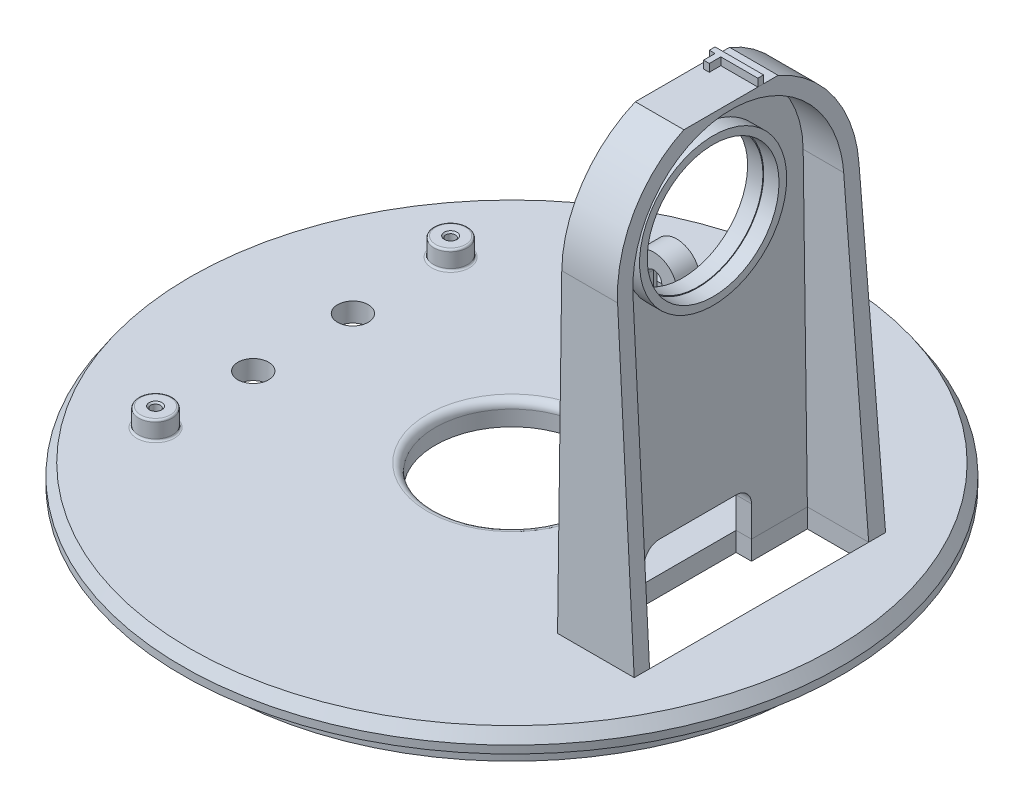
SolidWorks part; units mm, degrees
ref_plane "Plan de face" through (0, 0, 0) normal (0, 0, 1) x (1, 0, 0)
ref_plane "Plan de dessus" through (0, 0, 0) normal (0, 1, 0) x (1, 0, 0)
ref_plane "Plan de droite" through (0, 0, 0) normal (1, 0, 0) x (0, 0, -1)
sketch "Esquisse1" plane through (0, 0, 0) normal (1, 0, 0) x (0, 0, -1)
  line L0 (0, -26.723) -> (0, 41.89) construction
  line L1 (38.5, 0) -> (38.5, 4)
  line L2 (38.5, 4) -> (43, 4)
  line L3 (43, 4) -> (43, 5)
  line L4 (42, 6.5) -> (10, 6.5)
  line L5 (10, 6.5) -> (10, 3.5)
  line L6 (10, 3.5) -> (11, 3.5)
  line L7 (11, 3.5) -> (11, 4)
  line L8 (11, 4) -> (36.9, 4)
  line L9 (36.9, 4) -> (36.9, 0)
  line L10 (36.9, 0) -> (38.5, 0)
  line L11 (0, 0) -> (59.5639, 0) construction
  line L12 (43, 5) -> (42, 6.5)
  dimension "D1" = 10
  dimension "D2" = 0.5
  dimension "D3" = 1
  dimension "D4" = 43
  dimension "D5" = 4
  dimension "D6" = 1.6
  dimension "D7" = 4
  dimension "D8" = 4.5
  dimension "D9" = 2.5
  dimension "D10" = 1
  dimension "D11" = 1
revolve "Révolution1" add sketch "Esquisse1" angle 360 about L0
sketch "Esquisse2" plane through (0, 4, 0) normal (0, -1, 0) x (1, 0, 0)
  line L0 (0, 0) -> (0, -52.5963) construction
  line L1 (0, 0) -> (-60.9016, 0) construction
  line L2 (0, 0) -> (35.2447, -61.0455) construction
  circle A0 centre (0, 0) radius 16 construction
  circle A1 centre (-16, 0) radius 3
  dimension "D3" = 32
  dimension "D4" = 6
  dimension "D1" = 270
  dimension "D2" = 120
extrude "Boss.-Extru.1" add sketch "Esquisse2" along normal blind 3
pattern_circular "Répétition circulaire1" count 3 over 360 about axis through (0, 0, 0) along (0, 1, 0) of "Boss.-Extru.1"
sketch "Esquisse3" plane through (0, 6.5, 0) normal (0, 1, 0) x (1, 0, 0)
  line L0 (0, 0) -> (-69.5596, 0) construction
  line L1 (-22.25, 41.5926) -> (-22.25, -45.3568) construction
  line L2 (-27.25, 41.5926) -> (-27.25, -45.3568) construction
  circle A0 centre (-27.25, 19.25) radius 1
  circle A1 centre (-27.25, -19.25) radius 1
  circle A2 centre (-27.25, 6.5) radius 2
  circle A3 centre (-27.25, -6.5) radius 2
  dimension "D4" = 19.25
  dimension "D5" = 2
  dimension "D6" = 2
  dimension "D8" = 6.5
  dimension "D9" = 4
  dimension "D10" = 4
  dimension "D1" = 22.25
  dimension "D3" = 38.5
  dimension "D7" = 13
  dimension "D2" = 5
extrude "Enlèv. mat.-Extru.1" cut sketch "Esquisse3" against normal through all contours A2 | A3
ref_plane "Plan1" through (22.25, 0, 0) normal (1, 0, 0) x (0, 0, -1)
sketch "Esquisse4" plane through (22.25, 0, 0) normal (1, 0, 0) x (0, 0, -1)
  line L0 (-14.5, -8.6604) -> (-13.7488, 47.185) construction
  line L2 (0, -8.9601) -> (0, 72.3786) construction
  line L3 (-16.2962, 6.5) -> (-15.7486, 47.2119)
  line L4 (16.5, 6.5) -> (15.7486, 47.2119)
  line L5 (-16.4998, -8.6335) -> (-15.7486, 47.2119) construction
  line L6 (-16.2962, 6.5) -> (16.5, 6.5)
  line L7 (42, 6.5) -> (-42, 6.5) construction
  arc A0 (0, 60.75) -> (-13.7488, 47.185) centre (0, 47) ccw construction
  arc A1 (0, 62.75) -> (-15.7486, 47.2119) centre (0, 47) ccw
  arc A2 (0, 62.75) -> (15.7486, 47.2119) centre (0, 47) cw
  circle A3 centre (0, 47) radius 8.5
  point P2 (-14.2961, 6.5)
  dimension "D1" = 27.5
  dimension "D2" = 40.5
  dimension "D5" = 17
  dimension "D3" = 14.2961
  dimension "D6" = 16.5
  dimension "D4" = 2
extrude "Boss.-Extru.2" add sketch "Esquisse4" along normal blind 10 separate body
ref_plane "Plan2" through (0, 0, 16.2962) normal (0, 0, 1) x (1, 0, 0)
sketch "Esquisse7" plane through (32.25, 0, 0) normal (1, 0, 0) x (0, 0, -1)
  line L0 (-14.5, -8.6604) -> (-13.7488, 47.185) construction
  line L1 (-14.5, -8.6604) -> (-13.7488, 47.185)
  line L2 (0, -8.9601) -> (0, 72.3786) construction
  line L3 (0, -8.9601) -> (0, 72.3786) construction
  line L4 (14.5, -8.6604) -> (13.7488, 47.185)
  line L5 (-14.5, -8.6604) -> (14.5, -8.6604)
  arc A0 (0, 60.75) -> (-13.7488, 47.185) centre (0, 47) ccw construction
  arc A1 (13.7488, 47.185) -> (-13.7488, 47.185) centre (0, 47) ccw
extrude "Enlèv. mat.-Extru.3" cut sketch "Esquisse7" against normal blind 8
sketch "Esquisse6" plane through (0, 0, 16.2962) normal (0, 0, 1) x (1, 0, 0)
  line L0 (32.25, 6.5) -> (28.5, 62.75)
  line L1 (32.25, 62.75) -> (22.25, 62.75) construction
  line L2 (28.5, 62.75) -> (32.25, 62.75)
  line L3 (32.25, 62.75) -> (32.25, 6.5)
  line L4 (22.25, -44.7363) -> (22.25, 44.7363) construction
  dimension "D1" = 6.25
extrude "Enlèv. mat.-Extru.2" cut sketch "Esquisse6" against normal through all
sketch "Esquisse8" plane through (0, 6.5, 0) normal (0, 1, 0) x (-1, 0, 0)
  line L1 (-24.25, -14.2961) -> (-32.25, -14.2961)
  line L2 (-24.25, -14.2961) -> (-24.25, 14.2961)
  line L3 (-24.25, 14.2961) -> (-32.25, 14.2961)
  line L4 (-32.25, -14.2961) -> (-32.25, 14.2961)
extrude "Enlèv. mat.-Extru.4" cut sketch "Esquisse8" against normal through all
fillet "Congé1" radius 0.5 3 edges at (-16, 4, -3) (10.5981, 4, -12.3564) (5.4019, 4, 15.3564)
sketch "Esquisse9" plane through (0, 1, 0) normal (0, -1, 0) x (1, 0, 0)
  arc B0 (8.2491, -12.3772) -> (7.7509, -12.3772) centre (8, -12.3564) ccw
  arc B1 (7.4762, -12.4508) -> (7.0447, -12.7) centre (7.25, -12.5574) ccw
  arc B2 (6.8436, -12.9011) -> (6.5944, -13.3326) centre (6.701, -13.1064) ccw
  arc B3 (6.5208, -13.6073) -> (6.5208, -14.1055) centre (6.5, -13.8564) ccw
  arc B4 (6.5944, -14.3802) -> (6.8436, -14.8117) centre (6.701, -14.6064) ccw
  arc B5 (7.0447, -15.0128) -> (7.4762, -15.262) centre (7.25, -15.1554) ccw
  arc B6 (7.7509, -15.3356) -> (8.2491, -15.3356) centre (8, -15.3564) ccw
  arc B7 (8.5238, -15.262) -> (8.9553, -15.0128) centre (8.75, -15.1554) ccw
  arc B8 (9.1564, -14.8117) -> (9.4056, -14.3802) centre (9.299, -14.6064) ccw
  arc B9 (9.4792, -14.1055) -> (9.4792, -13.6073) centre (9.5, -13.8564) ccw
  arc B10 (9.4056, -13.3326) -> (9.1564, -12.9011) centre (9.299, -13.1064) ccw
  arc B11 (8.9553, -12.7) -> (8.5238, -12.4508) centre (8.75, -12.5574) ccw
  arc B12 (8.5238, -12.4508) -> (8.2491, -12.3772) centre (8, -13.8564) ccw
  arc B13 (7.7509, -12.3772) -> (7.4762, -12.4508) centre (8, -13.8564) ccw
  arc B14 (7.0447, -12.7) -> (6.8436, -12.9011) centre (8, -13.8564) ccw
  arc B15 (6.5944, -13.3326) -> (6.5208, -13.6073) centre (8, -13.8564) ccw
  arc B16 (6.5208, -14.1055) -> (6.5944, -14.3802) centre (8, -13.8564) ccw
  arc B17 (6.8436, -14.8117) -> (7.0447, -15.0128) centre (8, -13.8564) ccw
  arc B18 (7.4762, -15.262) -> (7.7509, -15.3356) centre (8, -13.8564) ccw
  arc B19 (8.2491, -15.3356) -> (8.5238, -15.262) centre (8, -13.8564) ccw
  arc B20 (8.9553, -15.0128) -> (9.1564, -14.8117) centre (8, -13.8564) ccw
  arc B21 (9.4056, -14.3802) -> (9.4792, -14.1055) centre (8, -13.8564) ccw
  arc B22 (9.4792, -13.6073) -> (9.4056, -13.3326) centre (8, -13.8564) ccw
  arc B23 (9.1564, -12.9011) -> (8.9553, -12.7) centre (8, -13.8564) ccw
  arc B24 (-16.1422, 1.4932) -> (-16.6235, 1.3643) centre (-16.3882, 1.4489) ccw
  arc B25 (-16.8698, 1.2221) -> (-17.2221, 0.8698) centre (-17.0607, 1.0607) ccw
  arc B26 (-17.3643, 0.6235) -> (-17.4932, 0.1422) centre (-17.4489, 0.3882) ccw
  arc B27 (-17.4932, -0.1422) -> (-17.3643, -0.6235) centre (-17.4489, -0.3882) ccw
  arc B28 (-17.2221, -0.8698) -> (-16.8698, -1.2221) centre (-17.0607, -1.0607) ccw
  arc B29 (-16.6235, -1.3643) -> (-16.1422, -1.4932) centre (-16.3882, -1.4489) ccw
  arc B30 (-15.8578, -1.4932) -> (-15.3765, -1.3643) centre (-15.6118, -1.4489) ccw
  arc B31 (-15.1302, -1.2221) -> (-14.7779, -0.8698) centre (-14.9393, -1.0607) ccw
  arc B32 (-14.6357, -0.6235) -> (-14.5068, -0.1422) centre (-14.5511, -0.3882) ccw
  arc B33 (-14.5068, 0.1422) -> (-14.6357, 0.6235) centre (-14.5511, 0.3882) ccw
  arc B34 (-14.7779, 0.8698) -> (-15.1302, 1.2221) centre (-14.9393, 1.0607) ccw
  arc B35 (-15.3765, 1.3643) -> (-15.8578, 1.4932) centre (-15.6118, 1.4489) ccw
  arc B36 (-15.8578, 1.4932) -> (-16.1422, 1.4932) centre (-16, 0) ccw
  arc B37 (-16.6235, 1.3643) -> (-16.8698, 1.2221) centre (-16, 0) ccw
  arc B38 (-17.2221, 0.8698) -> (-17.3643, 0.6235) centre (-16, 0) ccw
  arc B39 (-17.4932, 0.1422) -> (-17.4932, -0.1422) centre (-16, 0) ccw
  arc B40 (-17.3643, -0.6235) -> (-17.2221, -0.8698) centre (-16, 0) ccw
  arc B41 (-16.8698, -1.2221) -> (-16.6235, -1.3643) centre (-16, 0) ccw
  arc B42 (-16.1422, -1.4932) -> (-15.8578, -1.4932) centre (-16, 0) ccw
  arc B43 (-15.3765, -1.3643) -> (-15.1302, -1.2221) centre (-16, 0) ccw
  arc B44 (-14.7779, -0.8698) -> (-14.6357, -0.6235) centre (-16, 0) ccw
  arc B45 (-14.5068, -0.1422) -> (-14.5068, 0.1422) centre (-16, 0) ccw
  arc B46 (-14.6357, 0.6235) -> (-14.7779, 0.8698) centre (-16, 0) ccw
  arc B47 (-15.1302, 1.2221) -> (-15.3765, 1.3643) centre (-16, 0) ccw
  arc B48 (8.2491, 15.3356) -> (7.7509, 15.3356) centre (8, 15.3564) ccw
  arc B49 (7.4762, 15.262) -> (7.0447, 15.0128) centre (7.25, 15.1554) ccw
  arc B50 (6.8436, 14.8117) -> (6.5944, 14.3802) centre (6.701, 14.6064) ccw
  arc B51 (6.5208, 14.1055) -> (6.5208, 13.6073) centre (6.5, 13.8564) ccw
  arc B52 (6.5944, 13.3326) -> (6.8436, 12.9011) centre (6.701, 13.1064) ccw
  arc B53 (7.0447, 12.7) -> (7.4762, 12.4508) centre (7.25, 12.5574) ccw
  arc B54 (7.7509, 12.3772) -> (8.2491, 12.3772) centre (8, 12.3564) ccw
  arc B55 (8.5238, 12.4508) -> (8.9553, 12.7) centre (8.75, 12.5574) ccw
  arc B56 (9.1564, 12.9011) -> (9.4056, 13.3326) centre (9.299, 13.1064) ccw
  arc B57 (9.4792, 13.6073) -> (9.4792, 14.1055) centre (9.5, 13.8564) ccw
  arc B58 (9.4056, 14.3802) -> (9.1564, 14.8117) centre (9.299, 14.6064) ccw
  arc B59 (8.9553, 15.0128) -> (8.5238, 15.262) centre (8.75, 15.1554) ccw
  arc B60 (8.5238, 15.262) -> (8.2491, 15.3356) centre (8, 13.8564) ccw
  arc B61 (7.7509, 15.3356) -> (7.4762, 15.262) centre (8, 13.8564) ccw
  arc B62 (7.0447, 15.0128) -> (6.8436, 14.8117) centre (8, 13.8564) ccw
  arc B63 (6.5944, 14.3802) -> (6.5208, 14.1055) centre (8, 13.8564) ccw
  arc B64 (6.5208, 13.6073) -> (6.5944, 13.3326) centre (8, 13.8564) ccw
  arc B65 (6.8436, 12.9011) -> (7.0447, 12.7) centre (8, 13.8564) ccw
  arc B66 (7.4762, 12.4508) -> (7.7509, 12.3772) centre (8, 13.8564) ccw
  arc B67 (8.2491, 12.3772) -> (8.5238, 12.4508) centre (8, 13.8564) ccw
  arc B68 (8.9553, 12.7) -> (9.1564, 12.9011) centre (8, 13.8564) ccw
  arc B69 (9.4056, 13.3326) -> (9.4792, 13.6073) centre (8, 13.8564) ccw
  arc B70 (9.4792, 14.1055) -> (9.4056, 14.3802) centre (8, 13.8564) ccw
  arc B71 (9.1564, 14.8117) -> (8.9553, 15.0128) centre (8, 13.8564) ccw
sketch_block_instance "Bloc1-1"
sketch_block "Bloc1"
sketch_block_instance "Bloc1-2"
sketch_block_instance "Bloc1-3"
extrude "Enlèv. mat.-Extru.5" cut sketch "Esquisse9" against normal blind 5
sketch "Esquisse10" plane through (24.25, 0, 0) normal (1, 0, 0) x (0, 0, -1)
  line L0 (-7, 4) -> (7, 4)
  line L1 (-38.5, 4) -> (38.5, 4) construction
  line L2 (-7, 4) -> (-7, 10.5)
  line L4 (-5, 12.5) -> (5, 12.5)
  line L6 (7, 10.5) -> (7, 4)
  line L7 (-14.2961, 6.5) -> (14.2961, 6.5) construction
  arc A0 (5, 12.5) -> (7, 10.5) centre (5, 10.5) cw
  arc A1 (-5, 12.5) -> (-7, 10.5) centre (-5, 10.5) ccw
  point P11 (7, 12.5)
  point P16 (-7, 12.5)
  dimension "D3" = 2
  dimension "D1" = 14
  dimension "D2" = 7
  dimension "D4" = 6
extrude "Enlèv. mat.-Extru.6" cut sketch "Esquisse10" against normal up to surface (2 mm away) up to face at (22.25, 30.7405, -0.0509)
sketch "Esquisse11" plane through (0, 6.5, 0) normal (0, 1, 0) x (-1, 0, 0)
  circle A1 centre (27.25, -19.25) radius 1 construction
  circle A3 centre (27.25, -19.25) radius 1 construction
  circle A5 centre (27.25, 19.25) radius 1 construction
  circle A6 centre (27.25, 19.25) radius 1 construction
  circle A7 centre (27.25, -19.25) radius 2.2
  circle A8 centre (27.25, 19.25) radius 2.2
  dimension "D1" = 4.4
  dimension "D2" = 4.4
extrude "Boss.-Extru.3" add sketch "Esquisse11" along normal blind 2.4
fillet "Congé3" radius 1 1 edges at (0, 6.5, -10)
ref_plane "Plan3" through (0, 0, -27) normal (0, 0, 1) x (1, 0, 0)
sketch "Esquisse12" plane through (0, 0, -27) normal (0, 0, 1) x (1, 0, 0)
  line L0 (0, -6.546) -> (0, 45.9402) construction
  line L1 (42, 6.5) -> (-42, 6.5) construction
  line L2 (5.95, 6.5) -> (7.45, 6.5) construction
  line L3 (11, 6.5) -> (-11, 6.5) construction
  line L4 (11.05, 6.5) -> (11.05, 9.5) construction
  line L5 (5.95, 6.5) -> (5.95, 9.5) construction
  line L6 (5.45, 6.5) -> (5.45, 9.5)
  line L7 (11.55, 6.5) -> (11.55, 9.5)
  line L8 (5.45, 6.5) -> (5.45, 9.5) construction
  line L9 (11.55, 6.5) -> (11.55, 9.5) construction
  line L10 (5.45, 6.5) -> (7.45, 6.5)
  line L11 (7.45, 9.5) -> (7.45, 6.5)
  line L12 (9.55, 9.5) -> (9.55, 6.5)
  line L13 (9.55, 6.5) -> (11.05, 6.5) construction
  line L14 (9.55, 6.5) -> (11.55, 6.5)
  arc A0 (11.05, 9.5) -> (5.95, 9.5) centre (8.5, 9.5) ccw construction
  arc A1 (9.55, 9.5) -> (7.45, 9.5) centre (8.5, 9.5) ccw
  arc A2 (11.55, 9.5) -> (5.45, 9.5) centre (8.5, 9.5) ccw
  dimension "D2" = 5.1
  dimension "D6" = 2.1
  dimension "D1" = 3
  dimension "D3" = 8.5
  dimension "D4" = 5.1
  dimension "D5" = 2.55
  dimension "D7" = 0.5
extrude "Boss.-Extru.4" add sketch "Esquisse12" against normal blind 3
sketch "Esquisse13" plane through (0, 0, -30) normal (0, 0, -1) x (-1, 0, 0)
  line L0 (-5.95, 6.5) -> (-5.95, 9.5) construction
  line L1 (-11.05, 6.5) -> (-11.05, 9.5) construction
  line L3 (-5.95, 6.5) -> (-5.95, 9.5)
  line L4 (-11.05, 6.5) -> (-11.05, 9.5)
  line L5 (-11.05, 6.5) -> (-5.95, 6.5)
  arc A0 (-5.95, 9.5) -> (-11.05, 9.5) centre (-8.5, 9.5) ccw construction
  arc A1 (-5.95, 9.5) -> (-11.05, 9.5) centre (-8.5, 9.5) ccw
extrude "Enlèv. mat.-Extru.7" cut sketch "Esquisse13" against normal blind 2
mirror "Symétrie1" about plane through (0, 0, 0) normal (1, 0, 0) of "Enlèv. mat.-Extru.7", "Boss.-Extru.4"
sketch "Esquisse14" plane through (0, 6.5, 0) normal (0, 1, 0) x (1, 0, 0)
  line L1 (11.05, 30) -> (5.95, 30)
  line L2 (11.05, 30) -> (11.05, 28)
  line L3 (11.05, 28) -> (5.95, 28)
  line L4 (5.95, 30) -> (5.95, 28)
extrude "Enlèv. mat.-Extru.8" cut sketch "Esquisse14" against normal blind 10
mirror "Symétrie2" about plane through (0, 0, 0) normal (1, 0, 0) of "Enlèv. mat.-Extru.8"
hole_wizard "Trou taraudé M1.61" positions "Esquisse3D1" profile "Esquisse15" tap size "M1.6" standard "ISO" end condition through all
sketch3d "Esquisse3D1"
  line L0 (-27.25, 8.9, 19.25) -> (-27.25, 6.5, 19.25) construction
  line L1 (-27.25, 8.9, -19.25) -> (-27.25, 6.5, -19.25) construction
  point P0 (-27.25, 8.9, 19.25)
  point P4 (-27.25, 8.9, -19.25)
sketch "Esquisse15" plane through (-27.25, 8.9, 19.25) normal (1, 0, 0) x (0, 0, 1)
  line L0 (0, 0) -> (0, 8.9)
  line L1 (0, 8.9) -> (0.625, 8.9)
  line L2 (0.625, 8.9) -> (0.625, 0.2)
  line L3 (0.625, 0.2) -> (0.825, 0)
  line L5 (0.825, 0) -> (0, 0)
  line L6 (-0.625, 0.2) -> (-0.825, 0) construction
  line L11 (0, -6.35) -> (0, 107.95) construction
  dimension "Diamètre du trou pour taraudage jusqu'au prochain" = 1.25
  dimension "Profondeur du trou pour taraudage jusqu'au prochain" = 8.9
  dimension "Diamètre du fraisage entrant" = 1.65
  dimension "Angle du fraisage entrant" = 90
cosmetic thread "Filetage de perçage1" parameters "D2"=1.6
cosmetic thread "Filetage de perçage2" parameters "D2"=1.6
fillet "Congé4" radius 0.25 4 edges at (-27.25, 8.9, 21.45) (-27.25, 8.9, -17.05) (-27.25, 6.5, -17.05) (-27.25, 6.5, 21.45)
sketch "Esquisse16" plane through (24.25, 0, 0) normal (1, 0, 0) x (0, 0, -1)
  circle A0 centre (0, 47) radius 9.6
  circle A2 centre (0, 47) radius 8.6
  dimension "D1" = 1
extrude "Boss.-Extru.5" add sketch "Esquisse16" along normal blind 2
ref_plane "Plan4" through (0, 61.5, 0) normal (0, 1, 0) x (-1, 0, 0)
sketch "Esquisse17" plane through (0, 61.5, 0) normal (0, 1, 0) x (-1, 0, 0)
  line L0 (-32.25, 16.2962) -> (-22.25, 16.2962)
  line L1 (5.5, 16.2962) -> (-5.5, 16.2962) construction
  line L2 (-32.25, 16.2962) -> (-29.5359, 15.7486) construction
  line L3 (-22.25, 16.2962) -> (-22.25, -16.5) construction
  line L4 (-22.25, 16.2962) -> (-22.25, -15.7486)
  line L5 (-22.25, -15.7486) -> (-32.25, -15.7486)
  line L6 (-32.25, -15.7486) -> (-32.25, 16.2962)
  line L7 (-29.5359, -15.7486) -> (-22.25, -15.7486) construction
extrude "Enlèv. mat.-Extru.9" cut sketch "Esquisse17" along normal blind 10
sketch "Esquisse18" plane through (0, 61.5, 0) normal (0, 1, 0) x (-1, 0, 0)
  line L0 (-22.25, 8.5) -> (-22.25, -8.5) construction
  line L1 (-22.25, -4.25) -> (-28.5833, -4.25)
  line L2 (-22.25, -4.25) -> (-22.25, -3.5)
  line L3 (-22.25, -3.5) -> (-23, -3.5)
  line L4 (-28.5833, -4.25) -> (-28.5833, -3.5)
  line L5 (-28.5833, -6.1492) -> (-28.5833, 6.1492) construction
  line L6 (-23.75, -3.5) -> (-28.5833, -3.5)
  line L8 (-23, -3.5) -> (-23, -2)
  line L9 (-23, -2) -> (-23.75, -2)
  line L10 (-23.75, -3.5) -> (-23.75, -2)
  dimension "D1" = 0.75
  dimension "D2" = 3.5
  dimension "D3" = 0.75
  dimension "D4" = 1.5
  dimension "D5" = 1.5
extrude "Boss.-Extru.6" add sketch "Esquisse18" along normal blind 1
equation "\"D5@Esquisse12\" = \"D4@Esquisse12\"/2"
